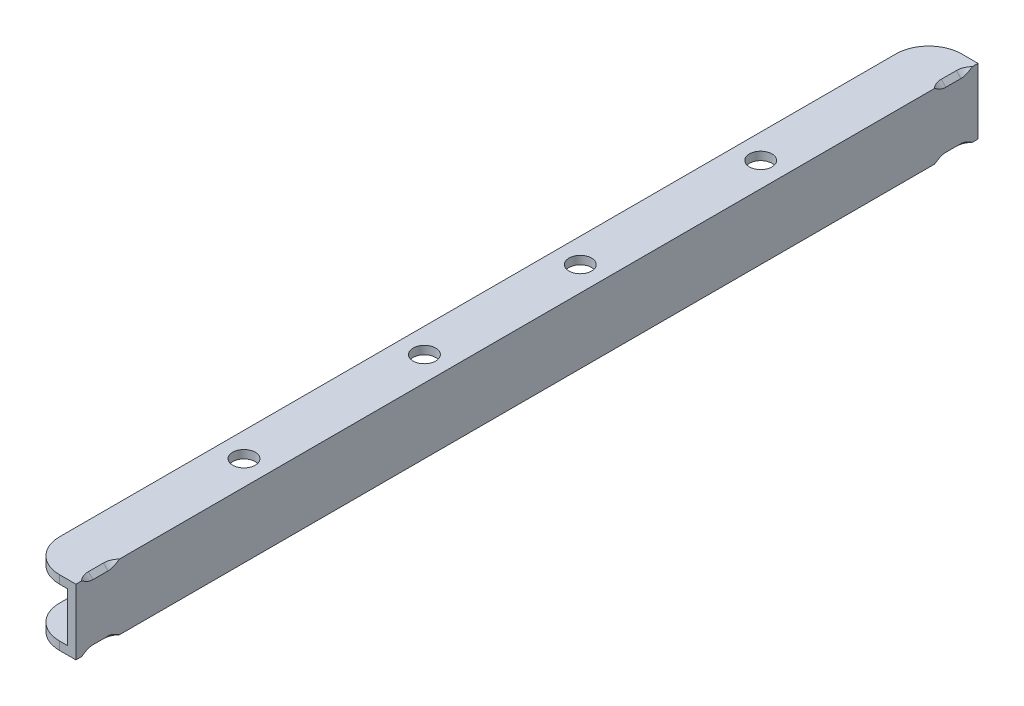
SolidWorks part; units mm, degrees
material "ASTM A36 Steel"
ref_plane "Front Plane" through (0, 0, 0) normal (0, 0, 1) x (1, 0, 0)
ref_plane "Top Plane" through (0, 0, 0) normal (0, 1, 0) x (1, 0, 0)
ref_plane "Right Plane" through (0, 0, 0) normal (1, 0, 0) x (0, 0, -1)
sketch "Sketch1" plane through (0, 0, 0) normal (0, 0, 1) x (1, 0, 0)
  line L0 (-19.05, 0) -> (0, 0)
  line L1 (0, 0) -> (0, 25.4)
  line L2 (0, 25.4) -> (-19.05, 25.4)
  line L3 (-19.05, 25.4) -> (-19.05, 22.225)
  line L4 (-19.05, 22.225) -> (-3.175, 22.225)
  line L5 (-3.175, 22.225) -> (-3.175, 3.175)
  line L6 (-3.175, 3.175) -> (-19.05, 3.175)
  line L7 (-19.05, 3.175) -> (-19.05, 0)
  dimension "D1" = 25.4
  dimension "D2" = 19.05
  dimension "D3" = 19.05
  dimension "D4" = 3.175
  dimension "D5" = 3.175
extrude "Boss-Extrude1" add sketch "Sketch1" along normal mid plane 349.25
sketch "Sketch3" plane through (0, 0, 0) normal (0, -1, 0) x (1, 0, 0)
  line L0 (-9.75, 0) -> (-59.779, 0) construction
  circle A0 centre (-9.525, -30.1752) radius 2.3495
  circle A1 centre (-9.525, -100.0252) radius 2.3495
  circle A2 centre (-9.525, 30.1752) radius 2.3495
  circle A3 centre (-9.525, 100.0252) radius 2.3495
  dimension "D1" = 4.699
  dimension "D3" = 69.85
  dimension "D2" = 30.1752
  dimension "D4" = 9.525
extrude "Cut-Extrude1" cut sketch "Sketch3" against normal up to next
sketch "Sketch4" plane through (0, 25.4, 0) normal (0, 1, 0) x (1, 0, 0)
  circle A0 centre (-9.525, -100.0252) radius 4.3688
  circle A1 centre (-9.525, -30.1752) radius 4.3688
  circle A2 centre (-9.525, 30.1752) radius 4.3688
  circle A3 centre (-9.525, 100.0252) radius 4.3688
  dimension "D1" = 8.7376
extrude "Cut-Extrude2" cut sketch "Sketch4" against normal up to next
fillet "Fillet1" radius 12.7 4 edges at (-19.05, 23.8125, -174.625) (-19.05, 1.5875, -174.625) (-19.05, 1.5875, 174.625) (-19.05, 23.8125, 174.625)
sketch "Sketch5" plane through (0, 25.4, 0) normal (0, 1, 0) x (1, 0, 0)
  line L0 (7.112, -155.829) -> (4.572, -155.829)
  line L1 (-1.778, -162.179) -> (-1.778, -168.021)
  line L2 (4.572, -174.371) -> (7.112, -174.371)
  line L3 (0, -174.625) -> (-6.35, -174.625) construction
  line L4 (0, -174.625) -> (0, 174.625) construction
  arc A0 (4.572, -155.829) -> (-1.778, -162.179) centre (4.572, -162.179) ccw
  arc A1 (-1.778, -168.021) -> (4.572, -174.371) centre (4.572, -168.021) ccw
  point P8 (-1.778, -165.1)
  dimension "D1" = 6.35
  dimension "D2" = 9.525
  dimension "D3" = 5.842
  dimension "D4" = 1.778
  dimension "D5" = 2.54
ref_plane "Plane1" through (7.112, 25.4, 174.371) normal (1, 0, 0) x (0, 0, -1)
sketch "Sketch6" plane through (7.112, 25.4, 174.371) normal (1, 0, 0) x (0, 0, -1)
  line L0 (-0.508, 0.508) -> (4.572, -4.572)
  line L1 (4.572, -4.572) -> (4.572, 0.508)
  line L2 (4.572, 0.508) -> (-0.508, 0.508)
  line L3 (4.572, -20.828) -> (4.572, -25.908)
  line L4 (4.572, -25.908) -> (-0.508, -25.908)
  line L5 (-0.508, -25.908) -> (4.572, -20.828)
  line L6 (-0.254, -25.4) -> (348.996, -25.4) construction
  point P6 (0, -25.4)
  dimension "D1" = 5.08
  dimension "D2" = 0.508
sweep "Cut-Sweep1" cut profiles "Sketch6" path "Sketch5"
mirror "Mirror1" about plane through (0, 0, 0) normal (0, 0, 1) of "Cut-Sweep1"
